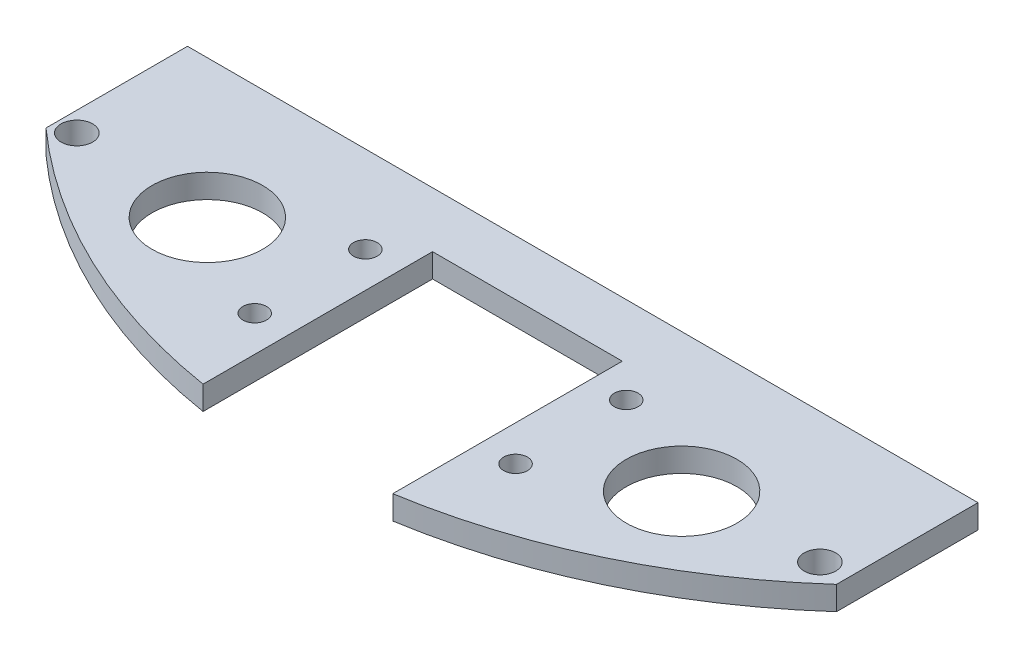
SolidWorks part; units mm, degrees
ref_plane "Alzado" through (0, 0, 0) normal (0, 0, 1) x (1, 0, 0)
ref_plane "Planta" through (0, 0, 0) normal (0, 1, 0) x (1, 0, 0)
ref_plane "Vista lateral" through (0, 0, 0) normal (1, 0, 0) x (0, 0, -1)
sketch "Croquis1" plane through (0, 0, 0) normal (0, 1, 0) x (1, 0, 0)
  circle A0 centre (0, 0) radius 75
  dimension "D1" = 150
extrude "Saliente-Extruir1" add sketch "Croquis1" along normal blind 3
sketch "Croquis3" plane through (0, 3, 0) normal (0, 1, 0) x (1, 0, 0)
  line L0 (0, 0) -> (0, 75) construction
  circle A0 centre (0, 0) radius 75 construction
sketch "Croquis4" plane through (0, 3, 0) normal (0, 1, 0) x (1, 0, 0)
  line L0 (0, -75) -> (0, -72) construction
  line L1 (0, 0) -> (0, 75) construction
  line L3 (0, 123.5152) -> (0, 0) construction
  line L20 (0, 0) -> (-134.6852, 77.7606) construction
  line L21 (0, 0) -> (124.3793, 71.8104) construction
  line L27 (1, -34) -> (0, -30) construction
  line L28 (0, -30) -> (-17.5, -30) construction
  line L29 (-17.5, -30) -> (-17.5, -7) construction
  line L31 (-17.5, -30) -> (17.5, -30)
  line L32 (-17.5, -30) -> (-17.5, -7)
  line L33 (-17.5, -7) -> (17.5, -7)
  line L34 (17.5, -30) -> (17.5, -7)
  circle A0 centre (0, 0) radius 75 construction
  circle A1 centre (0, 0) radius 75 construction
  point P22 (0, 0)
  point P25 (0, 0)
  point P26 (4.7408, 3.6006)
  point P32 (0, 0)
  dimension "D2" = 30
  dimension "D4" = 35
  dimension "D5" = 23
  dimension "D8" = 17.5
  dimension "D11" = 60
  dimension "D12" = 60
extrude "Cortar-Extruir9" cut sketch "Croquis4" against normal through all contours L32 L33 L34 L31
sketch "Croquis5" plane through (0, 3, 0) normal (0, 1, 0) x (1, 0, 0)
  line L0 (0, 75) -> (0, 55) construction
  line L1 (0, 0) -> (0, 75) construction
  line L2 (-75, 0) -> (-50, 0) construction
  line L3 (0, 55) -> (-53, 55)
  line L4 (0, 55) -> (0, 77)
  line L5 (0, 77) -> (-53, 77)
  line L6 (-53, 55) -> (-53, 77)
  line L7 (0, 55) -> (53, 55)
  line L8 (0, 55) -> (0, 77)
  line L9 (0, 77) -> (53, 77)
  line L10 (53, 55) -> (53, 77)
  line L11 (75, 0) -> (50, 0) construction
  line L13 (-50, 0) -> (-81, 0)
  line L14 (-50, 0) -> (-50, -56)
  line L15 (-50, -56) -> (-81, -56)
  line L16 (-81, 0) -> (-81, -56)
  line L17 (-50, 0) -> (-81, 0)
  line L18 (-50, 0) -> (-50, 55)
  line L19 (-50, 55) -> (-81, 55)
  line L20 (-81, 0) -> (-81, 55)
  line L21 (75, 0) -> (50, 0)
  line L22 (75, 0) -> (75, 55)
  line L23 (75, 55) -> (50, 55)
  line L24 (50, 0) -> (50, 55)
  line L25 (50, 0) -> (75, 0)
  line L26 (50, 0) -> (50, -56)
  line L27 (50, -56) -> (75, -56)
  line L28 (75, 0) -> (75, -56)
  circle A0 centre (0, 0) radius 75 construction
  circle M10 centre (0, 0) radius 75
  dimension "D1" = 20
  dimension "D2" = 53
  dimension "D3" = 22
  dimension "D4" = 53
  dimension "D5" = 25
  dimension "D6" = 25
  dimension "D7" = 55
  dimension "D8" = 31
  dimension "D9" = 56
  dimension "D10" = 56
extrude "Cortar-Extruir10" cut sketch "Croquis5" against normal through all contours L3 L4 M10 | L4 L7 M10 | L13 L18 L3 M10 | L15 L14 L13 M10 | L26 L27 L21 M10 | L24 L21 L7 M10
sketch "Croquis6" plane through (0, 3, 0) normal (0, 1, 0) x (1, 0, 0)
  line L0 (-20.5, -3) -> (-20.5, -38) construction
  line L1 (-17.5, -30) -> (-17.5, -7) construction
  line L2 (-50, -55.9017) -> (-50, 55) construction
  line L3 (-20.5, -3) -> (-50, -3)
  line L4 (-20.5, -3) -> (-20.5, -38)
  line L5 (-20.5, -38) -> (-50, -38)
  line L6 (-50, -3) -> (-50, -38)
  line L7 (50, 55) -> (-50, 55) construction
  line L8 (20.5, -3) -> (20.5, -38) construction
  line L9 (17.5, -30) -> (17.5, -7) construction
  line L10 (50, -55.9017) -> (50, 55) construction
  line L11 (20.5, -3) -> (50, -3)
  line L12 (20.5, -3) -> (20.5, -38)
  line L13 (20.5, -38) -> (50, -38)
  line L14 (50, -3) -> (50, -38)
  dimension "D1" = 3
  dimension "D2" = 35
  dimension "D3" = 58
  dimension "D4" = 3
  dimension "D5" = 35
  dimension "D6" = 58
extrude "Cortar-Extruir11" cut sketch "Croquis6" against normal through all
sketch "Croquis7" plane through (0, 3, 0) normal (0, 1, 0) x (1, 0, 0)
  line L2 (50, -3) -> (20.5, -3) construction
  line L3 (50, -3) -> (50, 55) construction
  line L4 (-20.5, -3) -> (-50, -3) construction
  circle A0 centre (-46.52, 47.87) radius 1.59
  circle A1 centre (-40.17, -0.46) radius 1.59
  circle A2 centre (36.03, 47.8) radius 1.59
  circle A3 centre (34.76, -0.46) radius 1.59
  dimension "D1" = 3.18
  dimension "D2" = 2.54
  dimension "D3" = 48.26
  dimension "D4" = 3.18
  dimension "D5" = 48.33
  dimension "D7" = 3.18
  dimension "D8" = 82.55
  dimension "D9" = 2.54
  dimension "D10" = 3.18
  dimension "D11" = 15.24
  dimension "D13" = 13.97
  dimension "D6" = 74.93
extrude "Cortar-Extruir12" cut sketch "Croquis7" against normal through all
sketch "Croquis8" plane through (0, 3, 0) normal (0, 1, 0) x (1, 0, 0)
  line L1 (0, -75) -> (-12, -75)
  line L2 (0, -75) -> (0, -45)
  line L3 (0, -45) -> (-12, -45)
  line L4 (-12, -75) -> (-12, -45)
  line L5 (0, -75) -> (12, -75)
  line L6 (0, -75) -> (0, -45)
  line L7 (0, -45) -> (12, -45)
  line L8 (12, -75) -> (12, -45)
  arc A0 (-50, -55.9017) -> (50, -55.9017) centre (0, 0) ccw construction
  arc M16 (-50, -55.9017) -> (50, -55.9017) centre (0, 0) ccw
  dimension "D1" = 12
  dimension "D2" = 12
  dimension "D3" = 30
extrude "Cortar-Extruir13" cut sketch "Croquis8" against normal through all contours L4 L2 L3 M16 | L8 L7 L2 M16
sketch "Croquis9" plane through (0, 3, 0) normal (0, 1, 0) x (1, 0, 0)
  line L0 (-87.2398, -55.4938) -> (93.5026, -55.4938) construction
  line L2 (-50, -38) -> (-50, -74.0338) construction
  line L3 (12, -74.0338) -> (-87.2398, -74.0338) construction
  line L4 (0, -74.0338) -> (0, 0) construction
  line L5 (-50, -38) -> (-20.5, -38) construction
  line L6 (20.5, -38) -> (50, -38) construction
  line L7 (50, -55.9017) -> (50, -38) construction
  line L8 (-12, -74.0338) -> (-12, -66.8438) construction
  line L9 (-12, -74.0338) -> (-12, -45) construction
  line L10 (-12, -66.8438) -> (-21.5, -66.8438) construction
  line L11 (-21.5, -66.8438) -> (-21.5, -71.8523) construction
  line L12 (-18.5, -68.8438) -> (20.5, -68.8438) construction
  circle A1 centre (-30, -55.4938) radius 7
  circle A2 centre (30, -55.4938) radius 7
  circle A3 centre (-47.5, -54.5) radius 2
  circle A4 centre (46.5, -54.5) radius 2
  arc A5 (-50, -55.9017) -> (-12, -74.0338) centre (0, 0) ccw construction
  dimension "D2" = 14
  dimension "D3" = 20
  dimension "D4" = 4
  dimension "D5" = 2.5
  dimension "D6" = 16.5
  dimension "D7" = 4
  dimension "D8" = 16.5
  dimension "D9" = 3.5
  dimension "D1" = 18.54
  dimension "D10" = 7.19
  dimension "D11" = 9.5
  dimension "D15" = 39
extrude "Cortar-Extruir15" cut sketch "Croquis9" against normal through all
sketch "Croquis10" plane through (0, 3, 0) normal (0, 1, 0) x (1, 0, 0)
  line L1 (-50, 55) -> (50, 55)
  line L2 (-50, 55) -> (-50, 65)
  line L3 (-50, 65) -> (50, 65)
  line L4 (50, 55) -> (50, 65)
  circle A0 centre (-45, 60) radius 2
  circle A1 centre (45, 60) radius 2
  dimension "D3" = 4
  dimension "D4" = 5
  dimension "D5" = 5
  dimension "D6" = 4
  dimension "D7" = 5
  dimension "D8" = 5
  dimension "D1" = 100
  dimension "D2" = 10
extrude "Saliente-Extruir2" add sketch "Croquis10" against normal blind 3
sketch "Croquis11" plane through (0, 3, 0) normal (0, 1, 0) x (1, 0, 0)
  line L0 (-12, -74.0338) -> (-12, -45) construction
  line L1 (12, -45) -> (-12, -45) construction
  line L2 (0, -74.4722) -> (0, -42.8881) construction
  line L3 (12, -74.0338) -> (12, -45) construction
  circle A0 centre (-16.5, -49) radius 1.5
  circle A1 centre (-16.5, -63) radius 1.5
  circle A2 centre (16.5, -63) radius 1.5
  circle A3 centre (16.5, -49) radius 1.5
  dimension "D1" = 3
  dimension "D2" = 4.5
  dimension "D3" = 4
  dimension "D4" = 3
  dimension "D5" = 14
  dimension "D6" = 4.5
  dimension "D7" = 4.5
  dimension "D8" = 4.5
  dimension "D9" = 4
  dimension "D10" = 14
  dimension "D11" = 3
  dimension "D12" = 3
extrude "Cortar-Extruir16" cut sketch "Croquis11" against normal through all
sketch "Croquis12" plane through (0, 3, 0) normal (0, 1, 0) x (1, 0, 0)
  line L1 (50, -38) -> (-50, -38)
  line L2 (50, -38) -> (50, 65)
  line L3 (50, 65) -> (-50, 65)
  line L4 (-50, -38) -> (-50, 65)
extrude "Cortar-Extruir17" cut sketch "Croquis12" against normal through all
